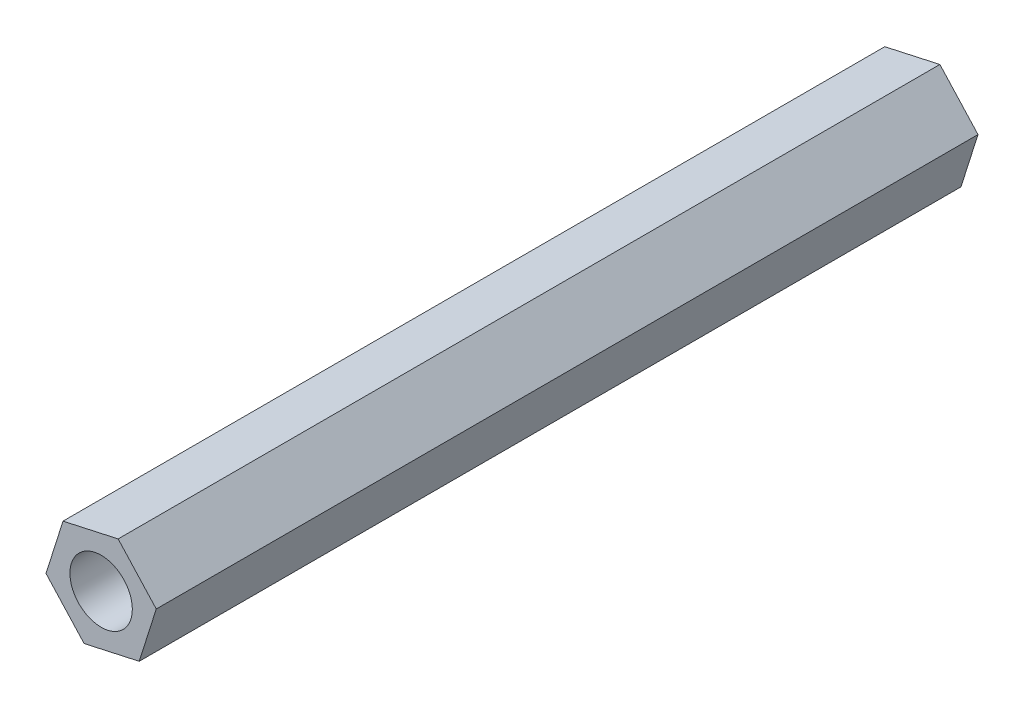
SolidWorks part; units mm, degrees
ref_plane "前视基准面" through (0, 0, 0) normal (0, 0, 1) x (1, 0, 0)
ref_plane "上视基准面" through (0, 0, 0) normal (0, 1, 0) x (1, 0, 0)
ref_plane "右视基准面" through (0, 0, 0) normal (1, 0, 0) x (0, 0, -1)
sketch "草图1" plane through (0, 0, 0) normal (0, 0, 1) x (1, 0, 0)
  line L1 (2.6498, 0.5847) -> (0.8185, 2.5871)
  line L2 (0.8185, 2.5871) -> (-1.8313, 2.0024)
  line L3 (-1.8313, 2.0024) -> (-2.6498, -0.5847)
  line L4 (-2.6498, -0.5847) -> (-0.8185, -2.5871)
  line L5 (-0.8185, -2.5871) -> (1.8313, -2.0024)
  line L6 (1.8313, -2.0024) -> (2.6498, 0.5847)
  circle A0 centre (0, 0) radius 2.35 construction
  circle A1 centre (0, 0) radius 1.5
extrude "凸台-拉伸1" add sketch "草图1" along normal blind 39.5
